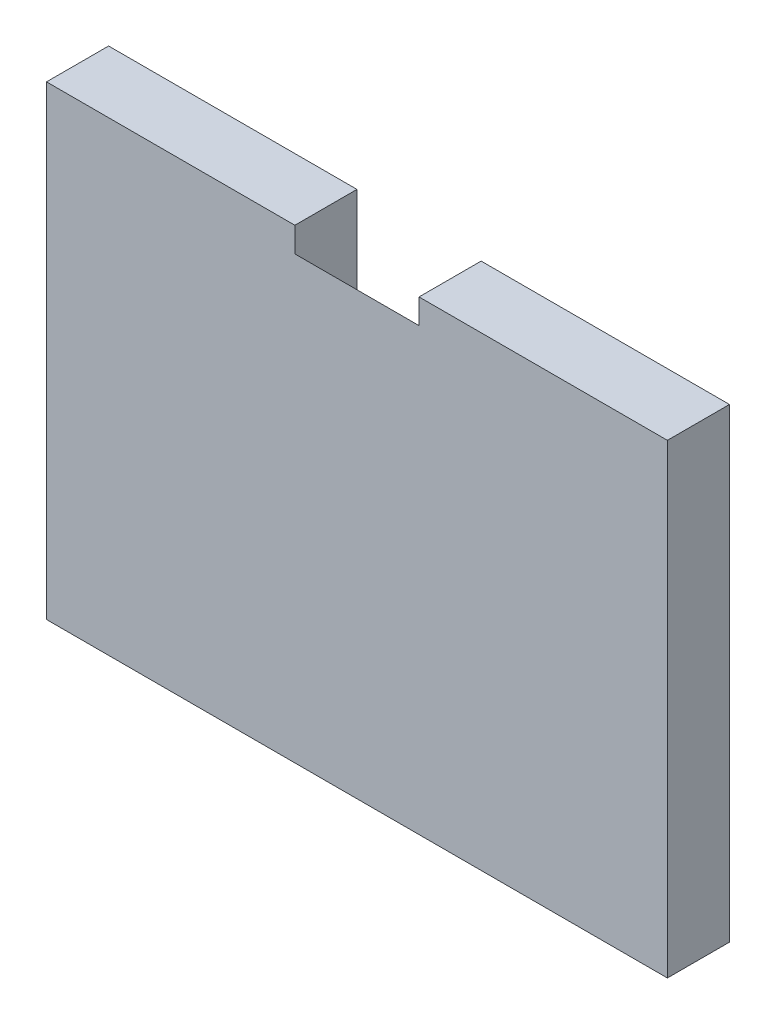
SolidWorks part; units mm, degrees
ref_plane "Plan de face" through (0, 0, 0) normal (0, 0, 1) x (1, 0, 0)
ref_plane "Plan de dessus" through (0, 0, 0) normal (0, 1, 0) x (1, 0, 0)
ref_plane "Plan de droite" through (0, 0, 0) normal (1, 0, 0) x (0, 0, -1)
sketch "Esquisse1" plane through (0, 0, 0) normal (0, 0, 1) x (1, 0, 0)
  line L0 (0, 37.5) -> (-10, 37.5) construction
  line L1 (-50, -37.5) -> (50, -37.5)
  line L2 (-50, -37.5) -> (-50, 37.5)
  line L3 (-50, 37.5) -> (-10, 37.5)
  line L4 (50, -37.5) -> (50, 37.5)
  line L5 (-50, -37.5) -> (50, 37.5) construction
  line L6 (-50, 37.5) -> (50, -37.5) construction
  line L7 (0, 37.5) -> (10, 37.5) construction
  line L8 (-10, 37.5) -> (-10, 33.5)
  line L9 (10, 37.5) -> (10, 33.5)
  line L10 (-10, 33.5) -> (10, 33.5)
  line L11 (10, 33.5) -> (10.1112, 33.6812)
  line L12 (10, 37.5) -> (50, 37.5)
  point P0 (0, 0)
  dimension "D1" = 100
  dimension "D2" = 75
  dimension "D3" = 10
  dimension "D4" = 10
  dimension "D5" = 4
  dimension "D6" = 4
extrude "Boss.-Extru.1" add sketch "Esquisse1" along normal blind 10 contours L9 L12 L4 L1 L2 L3 L8 L10
ref_plane "Plan2" through (50, 0, 0) normal (1, 0, 0) x (0, 0, -1)
sketch "Esquisse4" plane through (50, 0, 0) normal (1, 0, 0) x (0, 0, -1)
  line L0 (-10, 37.5) -> (-10, 33.5) construction
  line L1 (-10, 33.5) -> (0, 23.5)
  line L7 (0, 23.5) -> (0, 33.5)
  line L8 (0, -37.5) -> (0, 37.5) construction
  line L9 (0, 33.5) -> (-10, 33.5)
extrude "Enlèv. mat.-Extru.4" cut sketch "Esquisse4" against normal blind 60 contours L9 L1 L7
sketch "Esquisse11" plane through (50, 0, 0) normal (1, 0, 0) x (0, 0, -1)
  line L0 (-10, 33.5) -> (0, 33.5)
  line L1 (0, 33.5) -> (0, 23.5)
  line L2 (0, 23.5) -> (-10, 33.5)
extrude "Boss.-Extru.2" add sketch "Esquisse11" against normal blind 40
